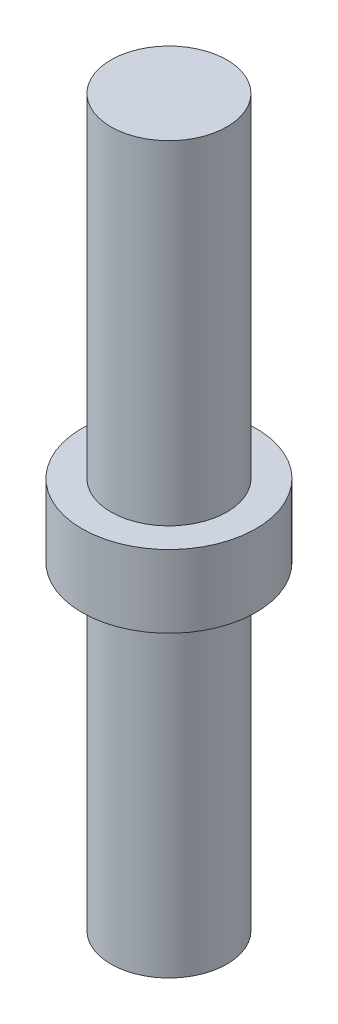
SolidWorks part; units mm, degrees
ref_plane "Front Plane" through (0, 0, 0) normal (0, 0, 1) x (1, 0, 0)
ref_plane "Top Plane" through (0, 0, 0) normal (0, 1, 0) x (1, 0, 0)
ref_plane "Right Plane" through (0, 0, 0) normal (1, 0, 0) x (0, 0, -1)
sketch "Sketch1" plane through (0, 0, 0) normal (0, 1, 0) x (1, 0, 0)
  circle A0 centre (0, 0) radius 4
  dimension "D1" = 8
extrude "Boss-Extrude1" add sketch "Sketch1" along normal blind 50
sketch "Sketch2" plane through (0, 50, 0) normal (0, 1, 0) x (1, 0, 0)
  circle A0 centre (0, 0) radius 6
  dimension "D1" = 12
extrude "Boss-Extrude2" add sketch "Sketch2" against normal blind 5 from offset 23 offset against normal yes
